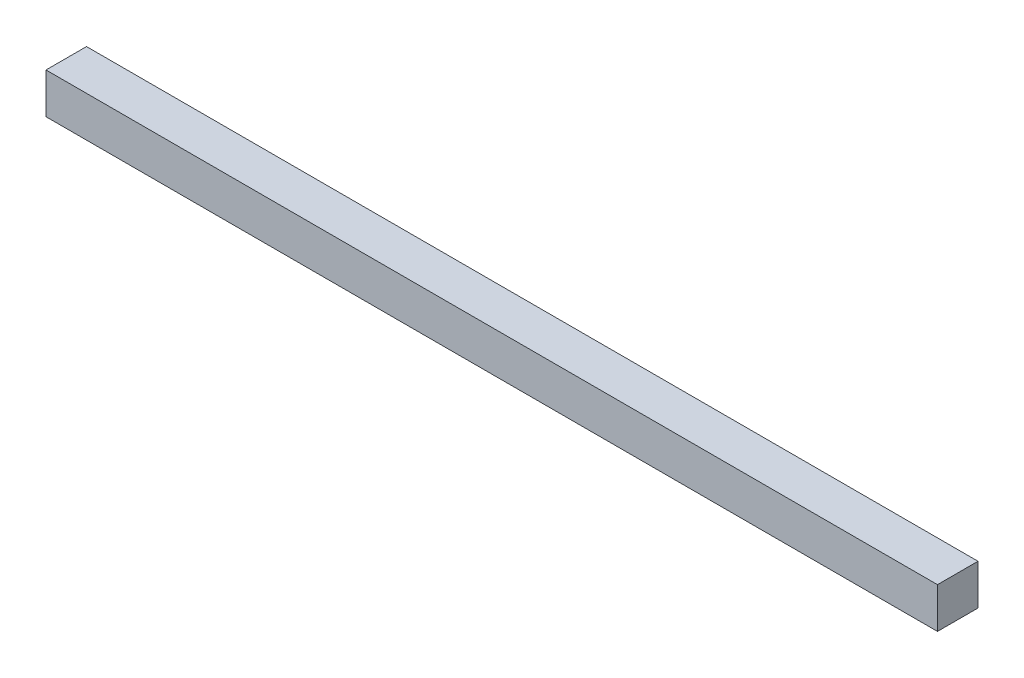
SolidWorks part; units mm, degrees
ref_plane "Front Plane" through (0, 0, 0) normal (0, 0, 1) x (1, 0, 0)
ref_plane "Top Plane" through (0, 0, 0) normal (0, 1, 0) x (1, 0, 0)
ref_plane "Right Plane" through (0, 0, 0) normal (1, 0, 0) x (0, 0, -1)
sketch "Sketch1" plane through (0, 0, 0) normal (1, 0, 0) x (0, 0, -1)
  line L1 (-25.4, 25.4) -> (25.4, 25.4)
  line L2 (-25.4, 25.4) -> (-25.4, -25.4)
  line L3 (-25.4, -25.4) -> (25.4, -25.4)
  line L4 (25.4, 25.4) -> (25.4, -25.4)
  line L5 (-25.4, 25.4) -> (25.4, -25.4) construction
  line L6 (-25.4, -25.4) -> (25.4, 25.4) construction
  point P0 (0, 0)
  dimension "D1" = 50.8
extrude "Boss-Extrude1" add sketch "Sketch1" along normal blind 1117.6
